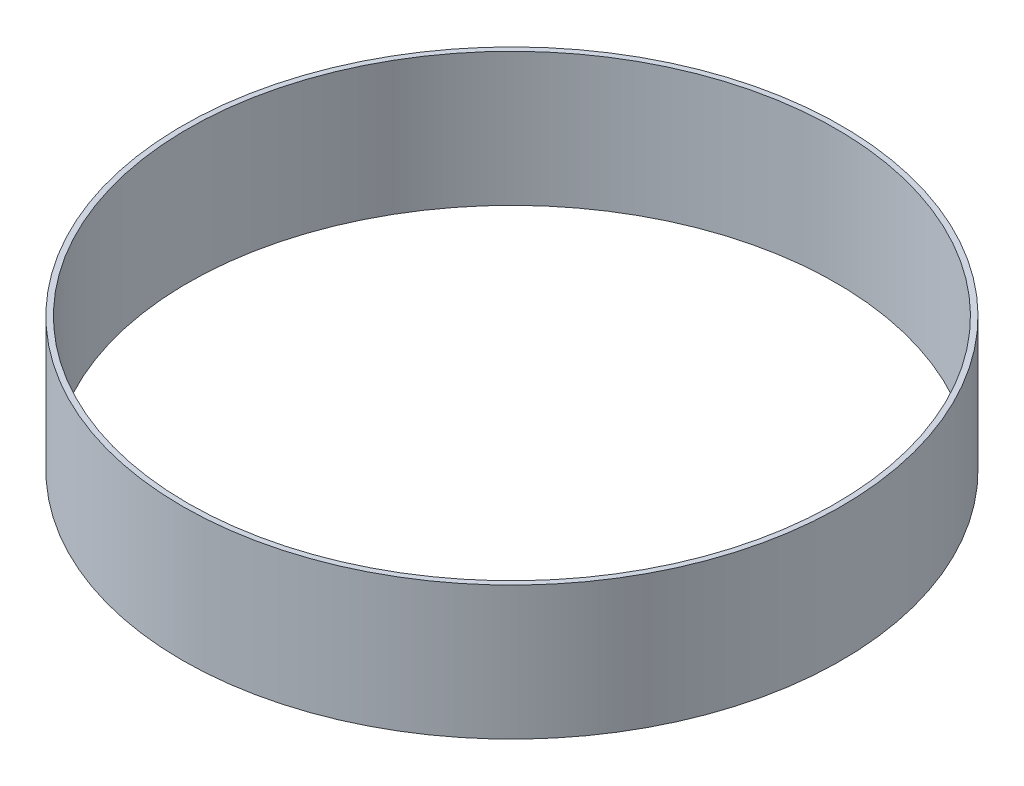
SolidWorks part; units mm, degrees
ref_plane "Front Plane" through (0, 0, 0) normal (0, 0, 1) x (1, 0, 0)
ref_plane "Top Plane" through (0, 0, 0) normal (0, 1, 0) x (1, 0, 0)
ref_plane "Right Plane" through (0, 0, 0) normal (1, 0, 0) x (0, 0, -1)
sketch "Sketch1" plane through (0, 0, 0) normal (0, 1, 0) x (1, 0, 0)
  circle A0 centre (0, 0) radius 121.5
  circle A1 centre (0, 0) radius 123.5
  dimension "D1" = 247
  dimension "D2" = 243
extrude "Boss-Extrude1" add sketch "Sketch1" along normal mid plane 50
scale "Scale1" [suppressed]
